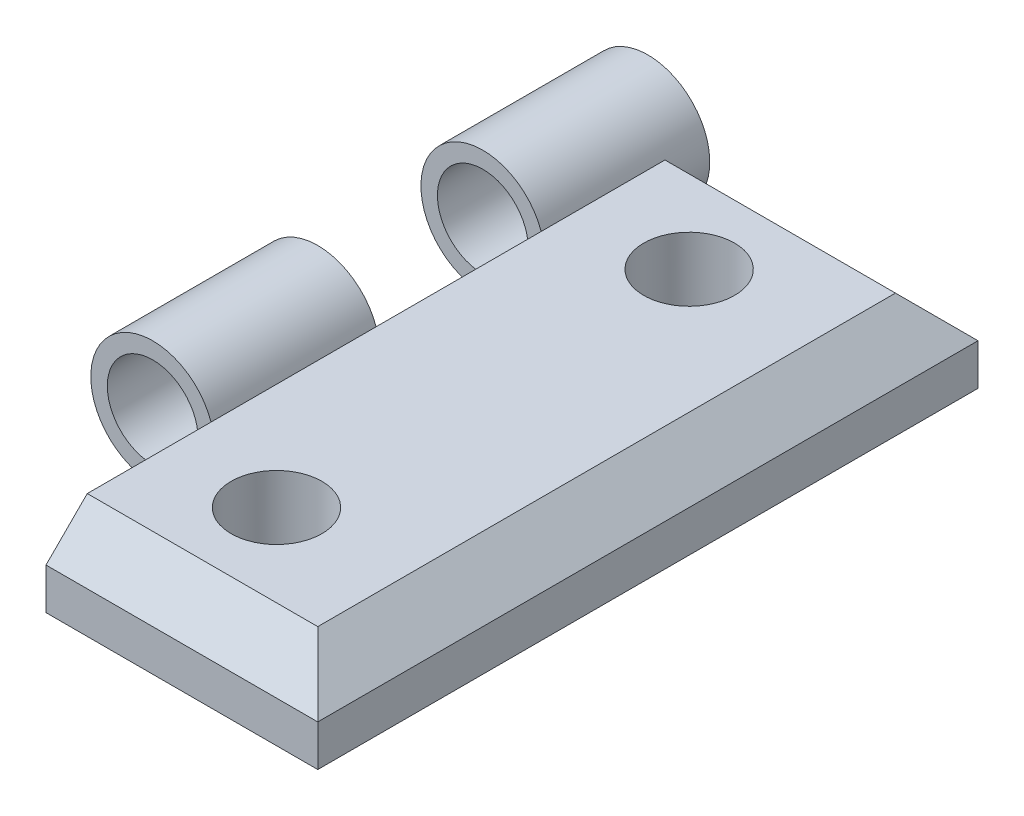
SolidWorks part; units mm, degrees
ref_plane "Ön Düzlem" through (0, 0, 0) normal (0, 0, 1) x (1, 0, 0)
ref_plane "Üst Düzlem" through (0, 0, 0) normal (0, 1, 0) x (1, 0, 0)
ref_plane "Sağ Düzlem" through (0, 0, 0) normal (1, 0, 0) x (0, 0, -1)
sketch "Çizim1" plane through (0, 0, 0) normal (0, 0, 1) x (1, 0, 0)
  line L0 (-4.5458, 5) -> (11.1525, 5)
  line L1 (11.1525, 5) -> (11.1525, 0)
  line L2 (11.1525, 0) -> (-8.8475, 0)
  line L4 (-5.312, 5) -> (-4.5458, 5)
  circle A0 centre (-8.8475, 3.75) radius 2.75
  arc A1 (-5.312, 5) -> (-8.8475, 0) centre (-8.8475, 3.75) ccw
  point P9 (3.9708, 3.75)
  point P10 (-8.8475, 3.75)
  dimension "D1" = 5.5
  dimension "D2" = 7.5
  dimension "D3" = 20
  dimension "D4" = 5
extrude "Yükseklik-Ekstrüzyon1" add sketch "Çizim1" along normal blind 40
sketch "Çizim2" plane through (0, 0, 0) normal (0, 1, 0) x (1, 0, 0)
  line L0 (11.1525, -40) -> (11.1525, 0) construction
  line L1 (11.1525, 0) -> (-5.312, 0) construction
  line L3 (-5.312, -40) -> (-12.5975, -40)
  line L4 (-12.5975, -40) -> (-12.5975, -30)
  line L5 (-12.5975, 0) -> (-12.5975, -40) construction
  line L6 (-12.5975, -30) -> (-5.312, -30)
  line L7 (-5.312, -40) -> (-5.312, 0) construction
  line L8 (-5.312, -30) -> (-5.312, -40)
  line L9 (-12.5975, -10) -> (-5.312, -10)
  line L10 (-5.312, -10) -> (-5.312, -20)
  line L11 (-5.312, -20) -> (-12.5975, -20)
  line L12 (-12.5975, -20) -> (-12.5975, -10)
  circle A0 centre (1.1525, -7.5) radius 2.75
  circle A1 centre (1.1525, -32.5) radius 2.75
  dimension "D1" = 5.5
  dimension "D2" = 5.5
  dimension "D3" = 7.5
  dimension "D4" = 25
  dimension "D5" = 10
  dimension "D6" = 10
  dimension "D7" = 10
  dimension "D8" = 10
  dimension "D9" = 10
extrude "Kes-Ekstrüzyon1" cut sketch "Çizim2" along normal blind 40
chamfer "Pah1" distance 2.5 3 edges at (2.9203, 5, 0) (11.1525, 5, 20) (2.9203, 5, 40)
